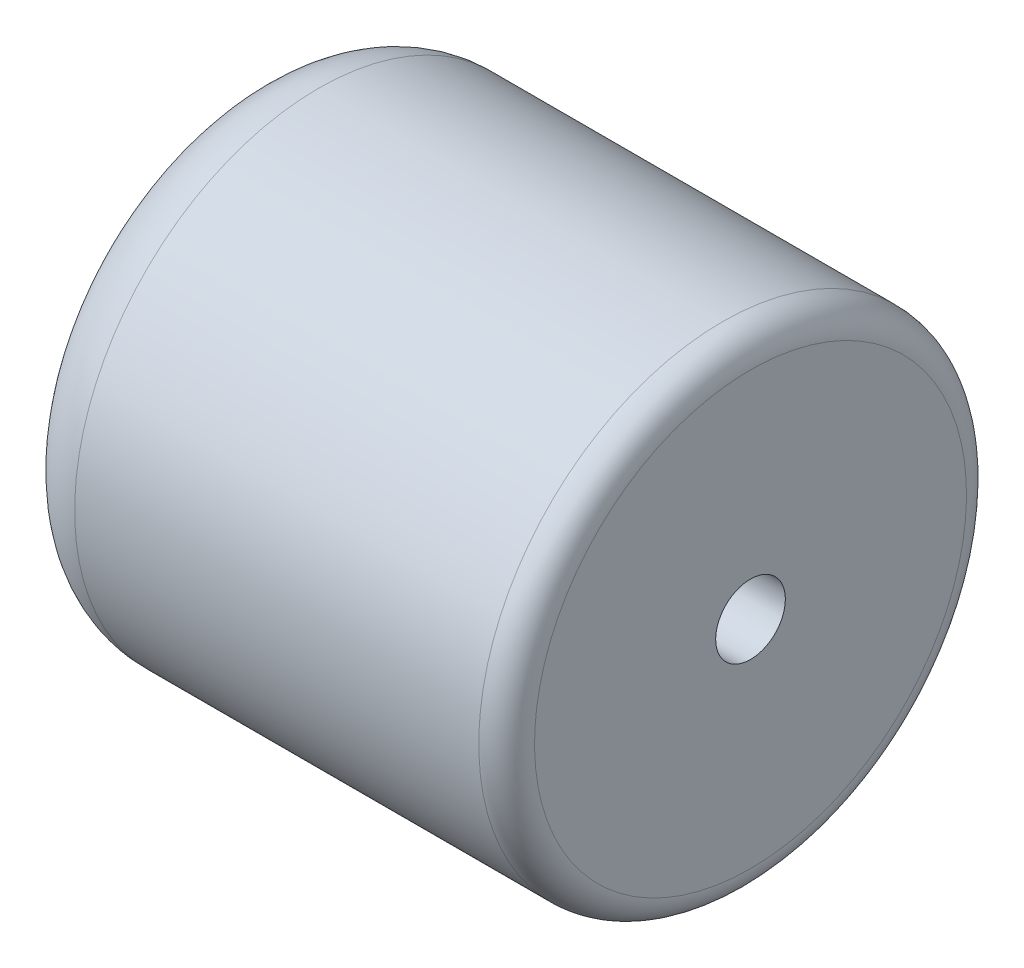
SolidWorks part; units mm, degrees
ref_plane "Front Plane" through (0, 0, 0) normal (0, 0, 1) x (1, 0, 0)
ref_plane "Top Plane" through (0, 0, 0) normal (0, 1, 0) x (1, 0, 0)
ref_plane "Right Plane" through (0, 0, 0) normal (1, 0, 0) x (0, 0, -1)
sketch "Sketch1" plane through (0, 0, 0) normal (0, 0, 1) x (1, 0, 0)
  line L0 (36, 0) -> (36.0378, 0)
  line L1 (0, 0) -> (26, 0)
  line L2 (0, 0) -> (0, -12.5)
  line L3 (5, -17.5) -> (34, -17.5)
  line L4 (36, -2.5) -> (36, -15.5)
  line L5 (36, 0) -> (52, 0)
  line L11 (36, -2.5) -> (26, -2.5)
  line L12 (26, 0) -> (26, -2.5)
  arc A0 (5, -17.5) -> (0, -12.5) centre (5, -12.5) cw
  arc A1 (34, -17.5) -> (36, -15.5) centre (34, -15.5) ccw
  point P7 (0, -17.5)
  point P10 (36, -17.5)
  dimension "D1" = 5
  dimension "D2" = 2
  dimension "B" = 36
  dimension "c/2" = 17.5
  dimension "D3" = 16
  dimension "D4" = 10
revolve "Revolve1" add sketch "Sketch1" angle 360 about L1
